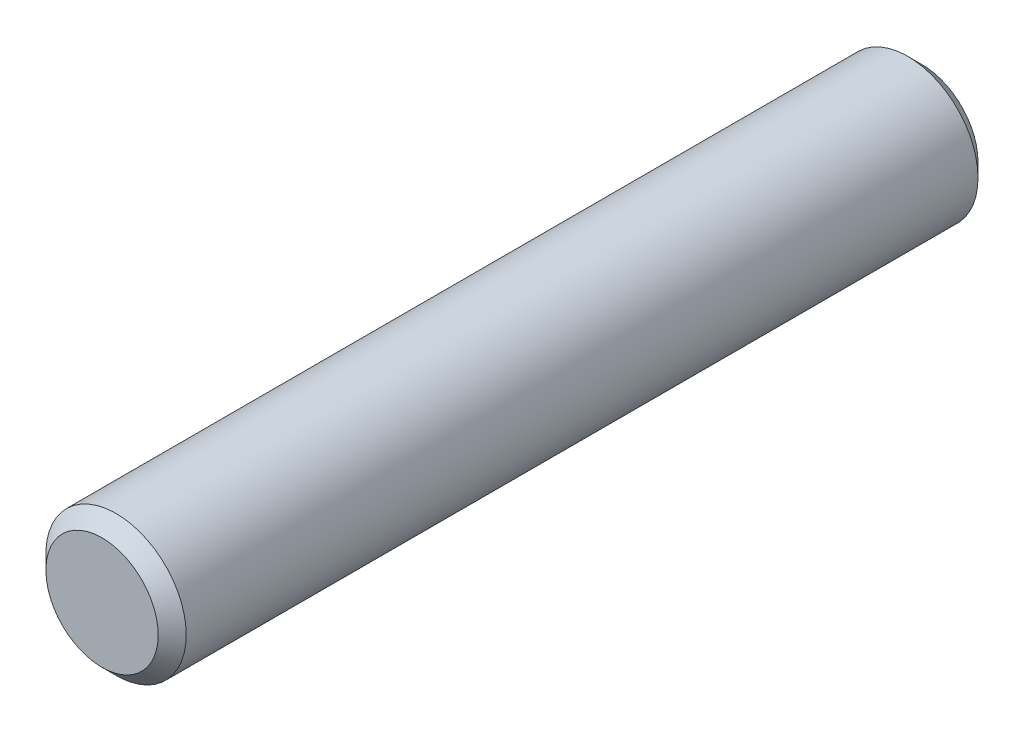
SolidWorks part; units mm, degrees
ref_plane "Front" through (0, 0, 0) normal (0, 0, 1) x (1, 0, 0)
ref_plane "Top" through (0, 0, 0) normal (0, 1, 0) x (1, 0, 0)
ref_plane "Right" through (0, 0, 0) normal (1, 0, 0) x (0, 0, -1)
sketch "Sketch1" plane through (0, 0, 0) normal (0, 0, 1) x (1, 0, 0)
  circle A0 centre (0, 0) radius 4
  dimension "dia" = 8
extrude "Extrude1" add sketch "Sketch1" along normal mid plane 46.736
sketch "Sketch2" plane through (0, 0, 0) normal (1, 0, 0) x (0, 0, -1)
  line L0 (23.368, 4) -> (-23.368, 4) construction
  point P0 (-23.368, 4)
  point P1 (23.368, 4)
  point P2 (-7.368, 4)
  point P5 (7.368, 4)
  dimension "D1" = 16
  dimension "D2" = 16
chamfer "Chamfer1" distance 0.8 angle 45 2 edges at (4, 0, -23.368) (4, 0, 23.368)
equation "\"D1@Chamfer1\" = \"dia@Sketch1\" * .1"
equation "\"D1@Sketch2\"=\"dia@sketch1\"*2"
equation "\"D2@Sketch2\"=\"D1@Sketch2\""
